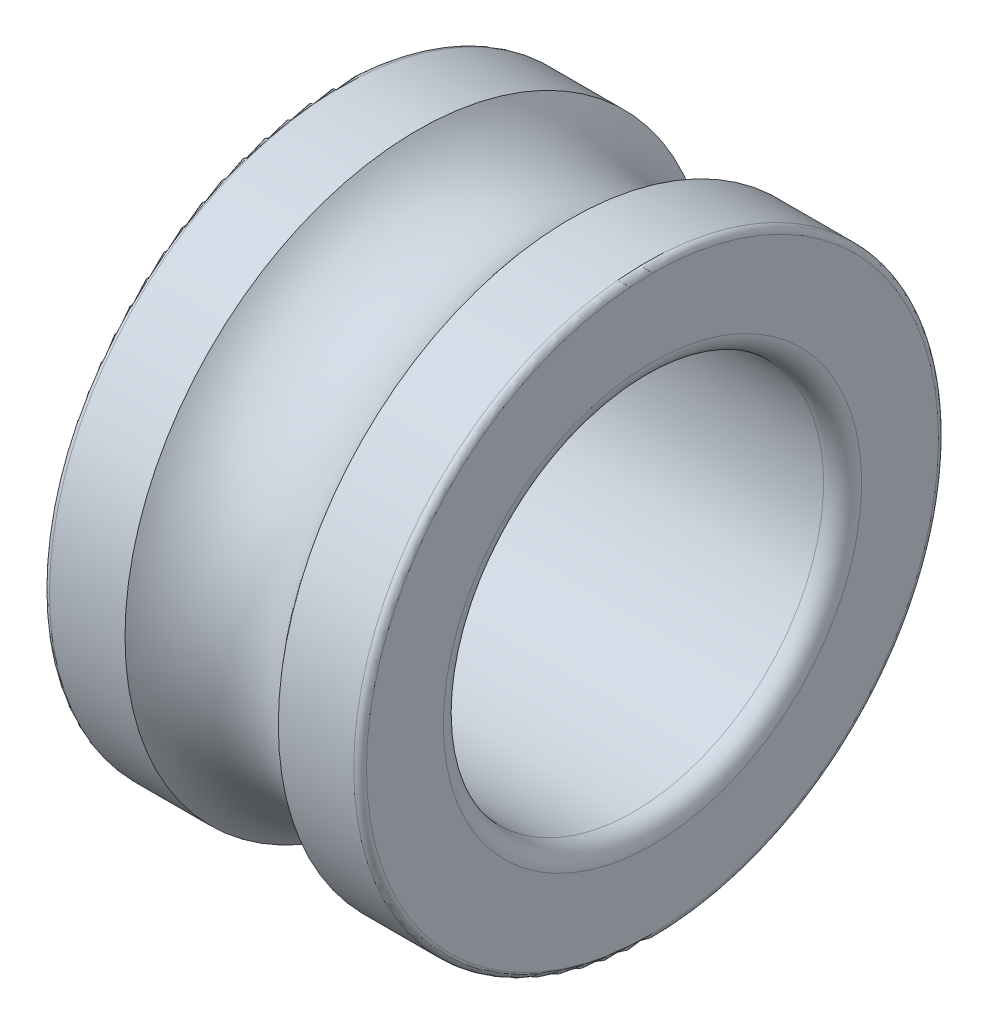
SolidWorks part; units mm, degrees
ref_plane "Plan de face" through (0, 0, 0) normal (0, 0, 1) x (1, 0, 0)
ref_plane "Plan de dessus" through (0, 0, 0) normal (0, 1, 0) x (1, 0, 0)
ref_plane "Plan de droite" through (0, 0, 0) normal (1, 0, 0) x (0, 0, -1)
ref_plane "Plan1" through (0, 0, 0) normal (0, 0, 1) x (1, 0, 0)
sketch "Esquisse1" plane through (0, 0, 0) normal (0, 0, 1) x (1, 0, 0)
  line L0 (0.6, 6) -> (9.4, 6)
  line L1 (10, 6.6) -> (10, 9.025)
  line L2 (9.8, 9.225) -> (7.4185, 9.225)
  line L3 (2.5815, 9.225) -> (0.2, 9.225)
  line L4 (0, 9.025) -> (0, 6.6)
  line L5 (100, 0) -> (-100, 0) construction
  arc A0 (0, 6.6) -> (0.6, 6) centre (0.6, 6.6) ccw
  arc A1 (9.4, 6) -> (10, 6.6) centre (9.4, 6.6) ccw
  arc A2 (10, 9.025) -> (9.8, 9.225) centre (9.8, 9.025) ccw
  arc A3 (7.4185, 9.225) -> (2.5815, 9.225) centre (5, 11) cw
  arc A4 (0.2, 9.225) -> (0, 9.025) centre (0.2, 9.025) ccw
revolve "Révolution1" add sketch "Esquisse1" angle 360 about L5
